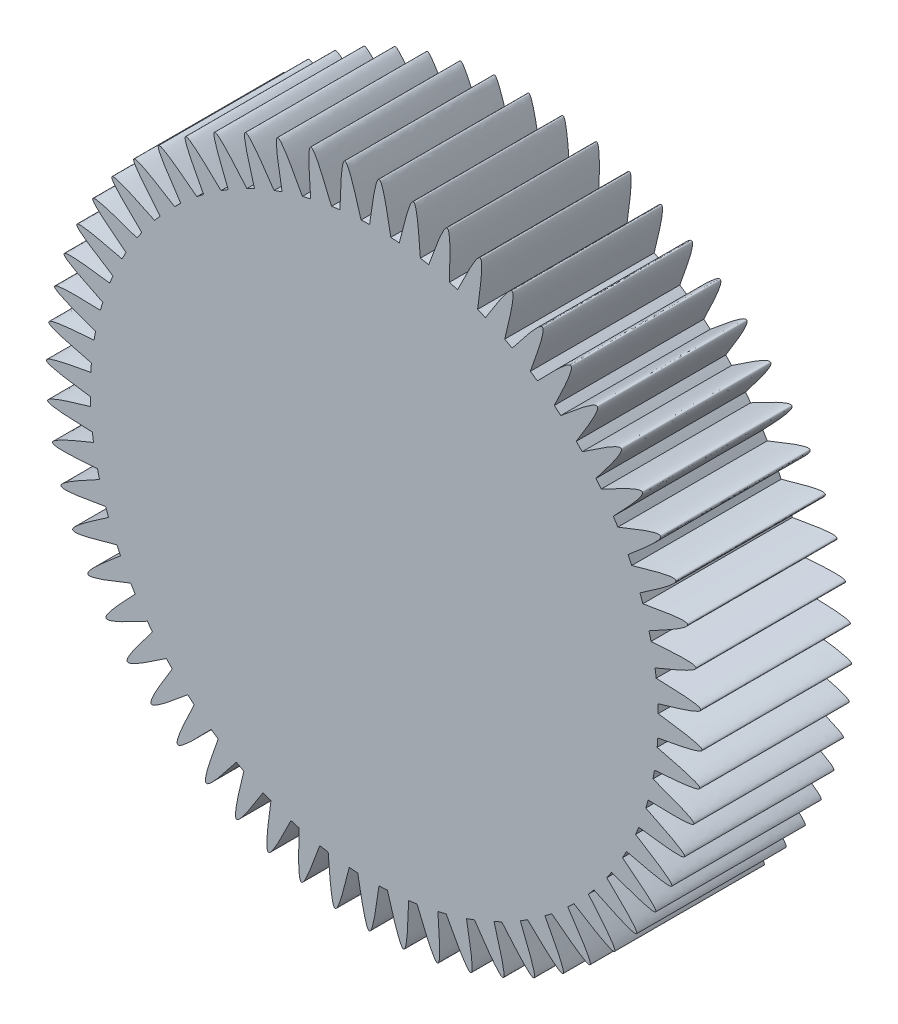
SolidWorks part; units mm, degrees
ref_plane "정면" through (0, 0, 0) normal (0, 0, 1) x (1, 0, 0)
ref_plane "윗면" through (0, 0, 0) normal (0, 1, 0) x (1, 0, 0)
ref_plane "우측면" through (0, 0, 0) normal (1, 0, 0) x (0, 0, -1)
sketch "스케치1" plane through (0, 0, 0) normal (0, 0, 1) x (1, 0, 0)
  circle A0 centre (0, 0) radius 19
  dimension "D1" = 38
extrude "보스-돌출1" add sketch "스케치1" along normal blind 10
sketch "스케치2" plane through (0, 0, 10) normal (0, 0, 1) x (1, 0, 0)
  circle A0 centre (0, 0) radius 19 construction
  arc A1 (-14.3283, 12.478) -> (-13.3549, 13.5147) centre (0, 0) ccw
  spline S0 degree 3 poles (-14.3283, 12.478) (-15.2784, 13.6055) (-17.1986, 15.8841) (-14.6449, 14.3099) (-13.3549, 13.5147) knots 0 0 0 0 0.494826 1 1 1 1
  point P3 (-14.3283, 12.478)
  point P5 (0, 0)
  point P9 (-16.0833, 14.9172)
  circle M1 centre (0, 0) radius 19
extrude "보스-돌출2" add sketch "스케치2" against normal blind 10 contours S0 M1
pattern_circular "원형 패턴1" count 60 every 6 about axis through (0, 0, 10) along (0, 0, -1) of "보스-돌출2"
